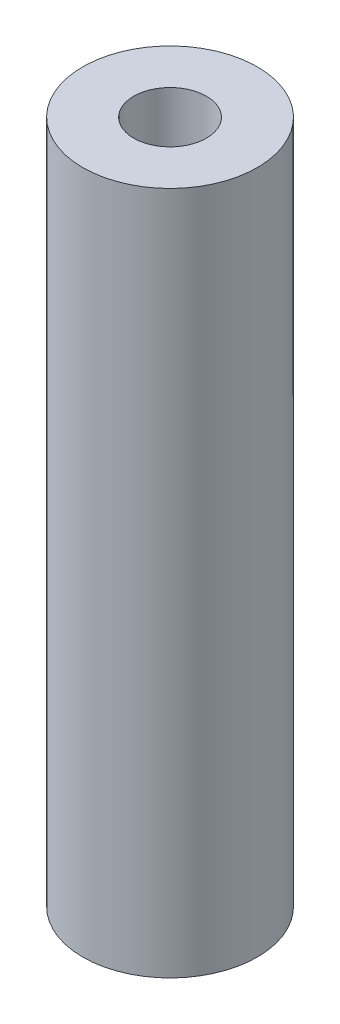
SolidWorks part; units mm, degrees
material "6061-T6 (SS)"
ref_plane "Front Plane" through (0, 0, 0) normal (0, 0, 1) x (1, 0, 0)
ref_plane "Top Plane" through (0, 0, 0) normal (0, 1, 0) x (1, 0, 0)
ref_plane "Right Plane" through (0, 0, 0) normal (1, 0, 0) x (0, 0, -1)
sketch "Sketch1" plane through (0, 0, 0) normal (0, 1, 0) x (1, 0, 0)
  circle A0 centre (0, 0) radius 3
  dimension "D1" = 6
extrude "Boss-Extrude1" add sketch "Sketch1" along normal blind 23.5
hole_wizard "Tap Drill for M3x0.5 Tap1" positions "Sketch2" profile "Sketch3" hole size "M3x0.5" standard "ANSI Metric" end condition up to next
sketch "Sketch2" plane through (0, 23.5, 0) normal (0, 1, 0) x (1, 0, 0)
  point P0 (0, 0)
sketch "Sketch3" plane through (0, 23.5, 0) normal (1, 0, 0) x (0, 0, 1)
  line L0 (0, 0) -> (0, 23.5)
  line L1 (0, 23.5) -> (1.25, 23.5)
  line L2 (1.25, 23.5) -> (1.25, 0)
  line L5 (1.25, 0) -> (0, 0)
  line L11 (0, -6.35) -> (0, 107.95) construction
  dimension "Thru Hole Dia." = 2.5
  dimension "Thru Hole Depth" = 23.5
